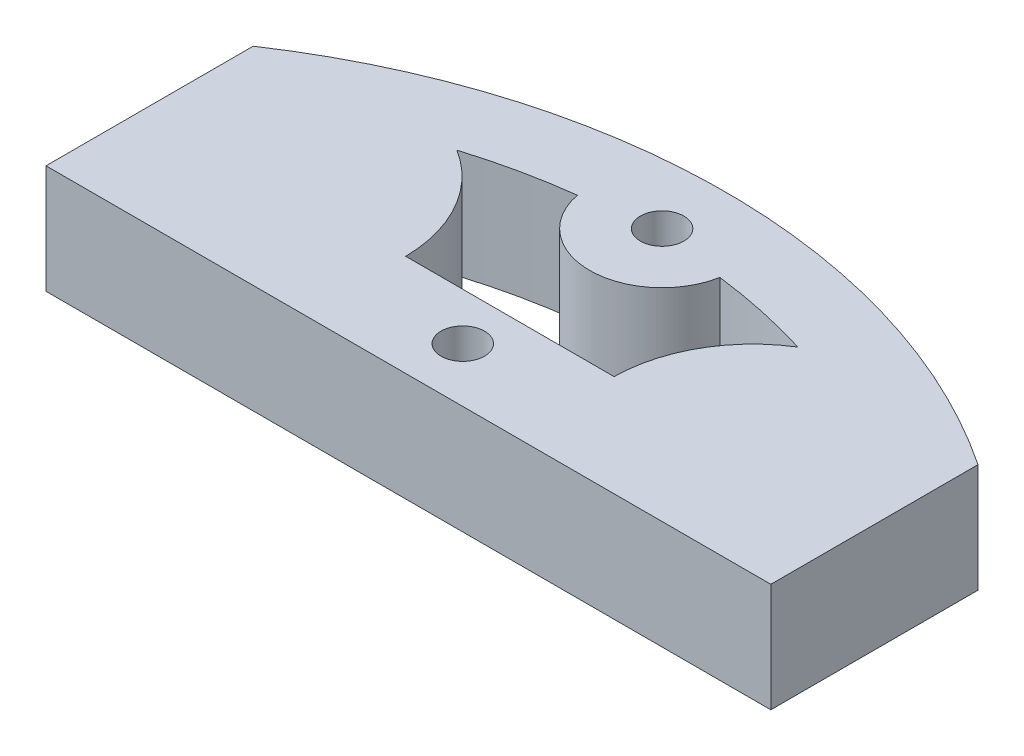
SolidWorks part; units mm, degrees
material "ABS"
ref_plane "Front Plane" through (0, 0, 0) normal (0, 0, 1) x (1, 0, 0)
ref_plane "Top Plane" through (0, 0, 0) normal (0, 1, 0) x (1, 0, 0)
ref_plane "Right Plane" through (0, 0, 0) normal (1, 0, 0) x (0, 0, -1)
sketch "Sketch1" plane through (0, 0, 0) normal (0, 1, 0) x (1, 0, 0)
  line L0 (0, -85) -> (-32.2211, -64.3879) construction
  line L1 (0, -85) -> (0, 0) construction
  arc A0 (36.2245, -62.2237) -> (-36.2245, -62.2237) centre (0, 0) ccw
  arc A1 (29.8119, -61.0352) -> (-29.8119, -61.0352) centre (0, -85) ccw
  arc A2 (36.2245, -62.2237) -> (29.8119, -61.0352) centre (33.7089, -57.9026) cw
  arc A3 (-29.8119, -61.0352) -> (-36.2245, -62.2237) centre (-33.7089, -57.9026) cw
  dimension "D1" = 144
  dimension "D2" = 76.5
  dimension "D4" = 5
  dimension "D3" = 85
extrude "Boss-Extrude1" add sketch "Sketch1" along normal mid plane 12
sketch "Sketch17" plane through (0, 6, 0) normal (0, 1, 0) x (1, 0, 0)
  line L3 (11.5013, 48.2) -> (-11.5013, 48.2)
  arc A0 (36.2245, -62.2237) -> (-36.2245, -62.2237) centre (0, 0) ccw construction
  arc A3 (-11.5013, 48.2) -> (-18.8249, 61.1688) centre (-27, 48) ccw
  arc A6 (18.8249, 61.1688) -> (11.5013, 48.2) centre (27, 48) ccw
  arc A9 (-7.861, 63.5154) -> (7.861, 63.5154) centre (0, 65) ccw
  arc A12 (-7.861, 63.5154) -> (-18.8249, 61.1688) centre (0, 0) ccw
  arc A15 (18.8249, 61.1688) -> (7.861, 63.5154) centre (0, 0) ccw
  dimension "D5" = 8
  dimension "D6" = 8
extrude "Cut-Extrude15" cut sketch "Sketch17" against normal through all
sketch "Sketch19" plane through (0, 6, 0) normal (0, 1, 0) x (1, 0, 0)
  line L1 (-40, 77) -> (40, 77)
  line L2 (-40, 77) -> (-40, 37)
  line L3 (-40, 37) -> (40, 37)
  line L4 (40, 77) -> (40, 37)
  line L5 (-40, 77) -> (40, 37) construction
  line L6 (-40, 37) -> (40, 77) construction
  arc A0 (-7.861, 63.5154) -> (7.861, 63.5154) centre (0, 65) ccw construction
  point P0 (0, 57)
  dimension "D1" = 80
  dimension "D2" = 40
extrude "Cut-Extrude16" cut sketch "Sketch19" against normal through all flip side to cut
sketch "Sketch20" plane through (0, 6, 0) normal (0, 1, 0) x (1, 0, 0)
  circle A0 centre (0, 65) radius 2.4
  circle A1 centre (0, 43) radius 2.4
  point P5 (0, 42.6705)
  dimension "D1" = 4.8
  dimension "D2" = 22
extrude "Cut-Extrude17" cut sketch "Sketch20" against normal through all
equation "\"smallPulleyTeeth\"= 30"
equation "\"largePulleyTeeth\"= 30"
equation "\"eighthThick\"= 3.0mm"
equation "\"sixteenthThick\" = 1.7mm"
equation "\"quarterThick\"=6.0mm"
equation "\"OD\" = 145mm"
equation "\"puckAngle\" = 60.5deg"
equation "\"puckDiam\" = 76.5mm"
equation "\"D2@Sketch1\"=\"puckDiam\""
equation "\"D1@Boss-Extrude1\"=\"eighthThick\"*4"
equation "\"axlePress\" = 5.9mm"
equation "\"press\" = 0.2mm"
equation "\"wheelClear\" = 0.3mm"
equation "\"10-32clear\" = 4.8mm"
equation "\"6-32clear\" = 3.3mm"
equation "\"8-32clear\" = 4.0mm"
equation "\"wheelHeight\" = 22mm"
equation "\"wheelWell\" = 65mm"
equation "\"puckDist\" = 85mm"
equation "\"scoopFillet\" = 5mm"
equation "\"4-40clear\" = 3.0mm"
equation "\"D3@Sketch1\"=\"puckDist\""
equation "\"D4@Sketch1\"=\"scoopFillet\""
equation "\"D3@Sketch6\"=\"10-32clear\""
equation "\"D2@Sketch8\"=\"eighthThick\""
equation "\"10-32tap\" = 4.45mm"
equation "\"ledSmall\" = 3.1mm"
equation "\"ledLarge\" = 4.2mm"
equation "\"ledLength\" = 4.2mm"
equation "\"D1@Sketch13\"=\"ledSmall\""
equation "\"D1@Cut-Extrude11\"=\"ledLength\""
equation "\"D1@Sketch14\"=\"ledLarge\""
equation "\"D1@Sketch20\"=\"10-32clear\""
